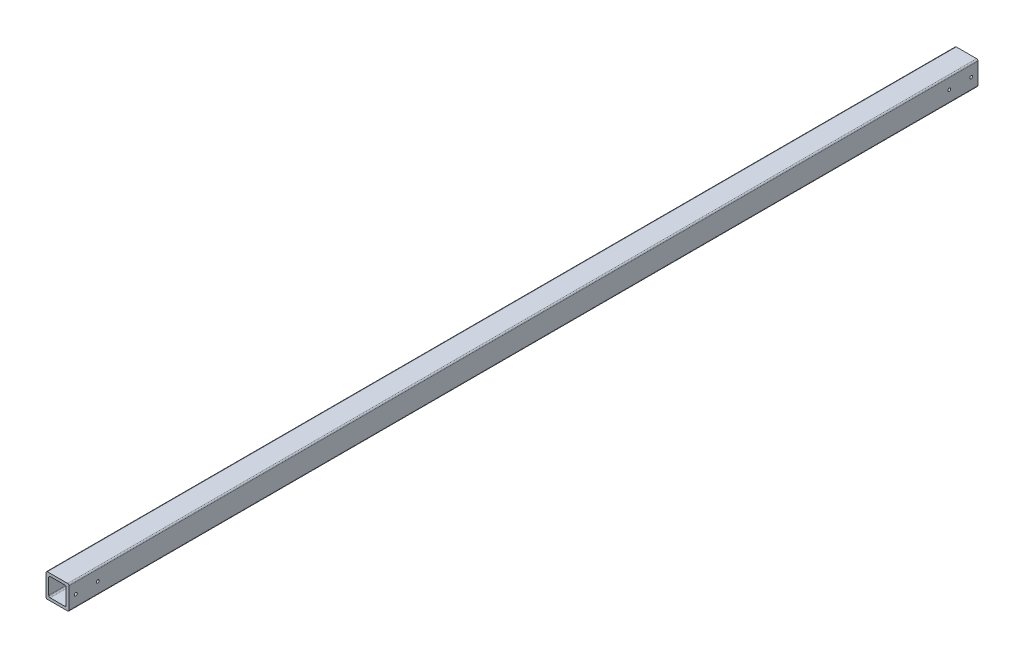
SolidWorks part; units mm, degrees
ref_plane "Front Plane" through (0, 0, 0) normal (0, 0, 1) x (1, 0, 0)
ref_plane "Top Plane" through (0, 0, 0) normal (0, 1, 0) x (1, 0, 0)
ref_plane "Right Plane" through (0, 0, 0) normal (1, 0, 0) x (0, 0, -1)
sketch "Main" plane through (0, 0, 0) normal (0, 1, 0) x (1, 0, 0)
  line L1 (-23.368, -844.55) -> (23.368, -844.55)
  line L2 (-23.368, -844.55) -> (-23.368, 844.55)
  line L3 (-23.368, 844.55) -> (23.368, 844.55)
  line L4 (23.368, -844.55) -> (23.368, 844.55)
  line L5 (-23.368, -844.55) -> (23.368, 844.55) construction
  line L6 (-23.368, 844.55) -> (23.368, -844.55) construction
  point P0 (0, 0)
  dimension "D1" = 1689.1
  dimension "D2" = 46.736
extrude "Extrude-Main" add sketch "Main" along normal blind 44.45
sketch "Main Cut" plane through (0, 0, 844.55) normal (0, 0, 1) x (1, 0, 0)
  line L0 (13.97, 5.08) -> (23.368, 5.08) construction
  line L5 (23.368, 44.45) -> (23.368, 0) construction
  line L7 (-23.368, 0) -> (23.368, 0) construction
  line L8 (-23.368, 44.45) -> (23.368, 44.45) construction
  line L9 (13.97, 5.08) -> (-18.288, 5.08)
  line L10 (13.97, 5.08) -> (13.97, 39.37)
  line L11 (13.97, 39.37) -> (-18.288, 39.37)
  line L12 (-18.288, 5.08) -> (-18.288, 39.37)
  line L13 (-23.368, 44.45) -> (-23.368, 0) construction
  dimension "D1" = 5.08
  dimension "D2" = 5.08
  dimension "D3" = 5.08
extrude "Cut-Main" cut sketch "Main Cut" against normal through all
sketch "Sketch1" plane through (0, 0, 844.55) normal (0, 0, 1) x (1, 0, 0)
  line L0 (-23.368, 44.45) -> (23.368, 44.45) construction
  line L1 (19.431, 44.45) -> (23.368, 44.45)
  line L2 (19.431, 44.45) -> (19.431, 0)
  line L3 (19.431, 0) -> (23.368, 0)
  line L4 (23.368, 44.45) -> (23.368, 0)
  dimension "D1" = 3.937
extrude "Cut-Extrude1" cut sketch "Sketch1" against normal through all
sketch "Sketch2" plane through (13.97, 0, 0) normal (-1, 0, 0) x (0, 0, 1)
  line L0 (844.55, 22.225) -> (-844.55, 22.225) construction
  line L1 (844.55, 5.08) -> (844.55, 39.37) construction
  line L2 (-844.55, 5.08) -> (-844.55, 39.37) construction
  line L3 (0, 44.45) -> (0, 0) construction
  line L4 (-844.55, 44.45) -> (844.55, 44.45) construction
  point P6 (-831.85, 22.225)
  point P7 (-791.21, 22.225)
  point P13 (791.21, 22.225)
  point P14 (831.85, 22.225)
  dimension "D1" = 12.7
  dimension "D2" = 53.34
hole_wizard "#4 (0.209) Diameter Hole2" positions "Sketch2" profile "Sketch5" hole size "#4" standard "ANSI Inch"
sketch "Sketch5" plane through (13.97, 22.225, 831.85) normal (0, 1, 0) x (0, 0, 1)
  line L0 (0, 0) -> (0, 5.461)
  line L1 (0, 5.461) -> (2.6543, 5.461)
  line L2 (2.6543, 5.461) -> (2.6543, 0)
  line L5 (2.6543, 0) -> (0, 0)
  line L11 (0, -6.35) -> (0, 107.95) construction
  dimension "Thru Hole Dia." = 5.3086
  dimension "Thru Hole Depth" = 5.461
fillet "Fillet1" radius 2.54 8 edges at (-18.288, 39.37, 0) (13.97, 39.37, 0) (13.97, 5.08, 0) (-18.288, 5.08, 0) (19.431, 0, 0) (-23.368, 0, 0) (19.431, 44.45, 0) (-23.368, 44.45, 0)
